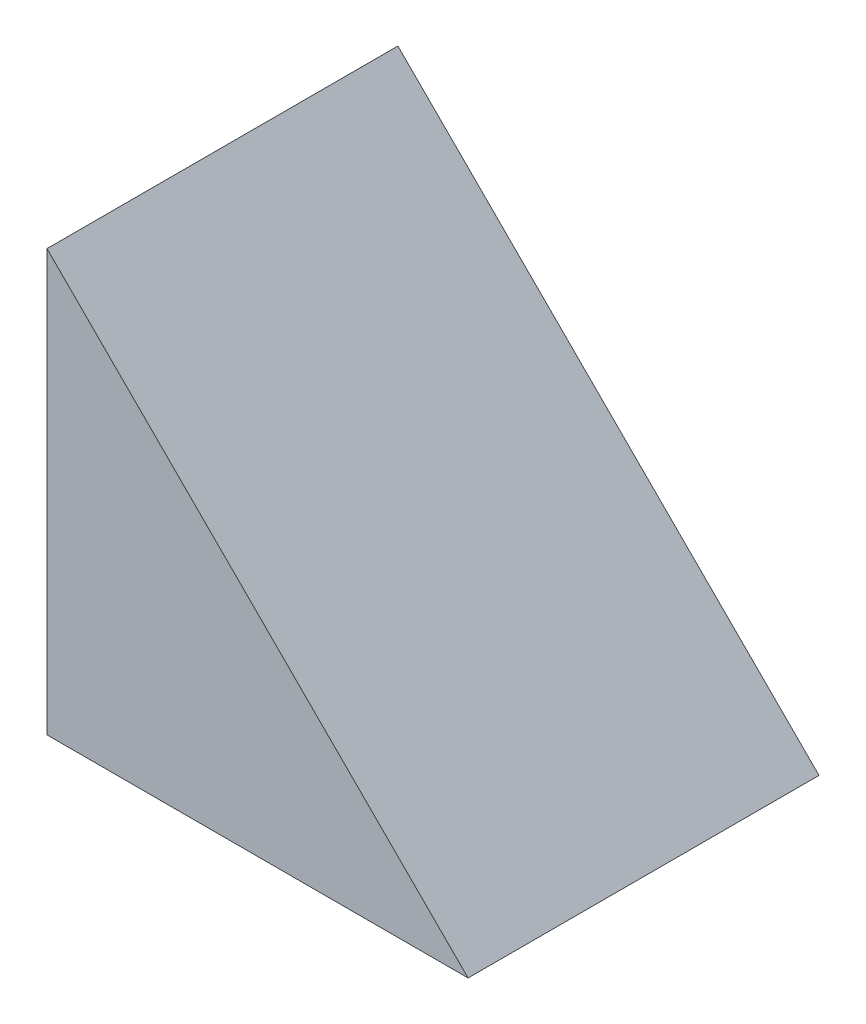
SolidWorks part; units mm, degrees
material "轻木"
ref_plane "Front" through (0, 0, 0) normal (0, 0, 1) x (1, 0, 0)
ref_plane "Top" through (0, 0, 0) normal (0, 1, 0) x (1, 0, 0)
ref_plane "Right" through (0, 0, 0) normal (1, 0, 0) x (0, 0, -1)
sketch "草图1" plane through (0, 0, 0) normal (0, 0, 1) x (1, 0, 0)
  line L0 (0, 0) -> (76.2, 0)
  line L1 (76.2, 0) -> (0, 76.2)
  line L2 (0, 76.2) -> (0, 0)
  dimension "D1" = 76.2
  dimension "D2" = 76.2
extrude "凸台-拉伸1" add sketch "草图1" along normal blind 63.5
